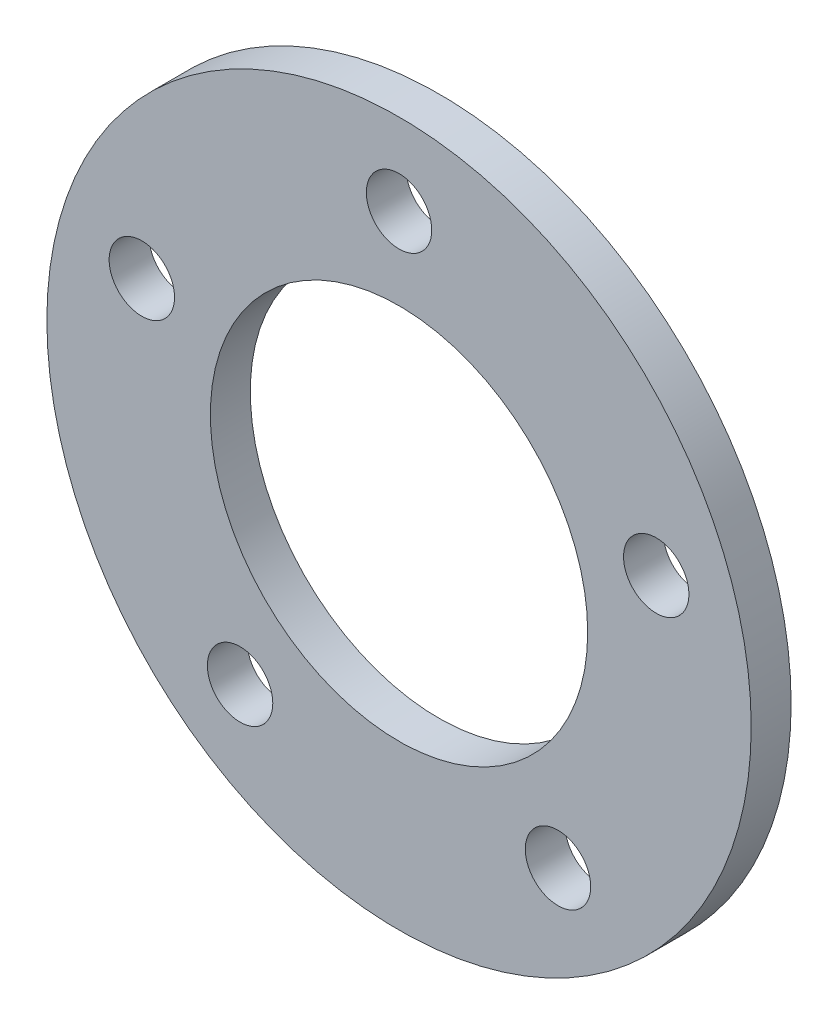
SolidWorks part; units mm, degrees
material "6061 Alloy"
ref_plane "Front Plane" through (0, 0, 0) normal (0, 0, 1) x (1, 0, 0)
ref_plane "Top Plane" through (0, 0, 0) normal (0, 1, 0) x (1, 0, 0)
ref_plane "Right Plane" through (0, 0, 0) normal (1, 0, 0) x (0, 0, -1)
sketch "Sketch1" plane through (0, 0, 0) normal (0, 0, 1) x (1, 0, 0)
  line L0 (0, 0) -> (0, 21.5) construction
  circle A0 centre (0, 0) radius 15
  circle A1 centre (0, 0) radius 28
  circle A2 centre (0, 21.5) radius 2.6
  circle A3 centre (20.4477, 6.6439) radius 2.6
  circle A4 centre (12.6374, -17.3939) radius 2.6
  circle A5 centre (-12.6374, -17.3939) radius 2.6
  circle A6 centre (-20.4477, 6.6439) radius 2.6
  dimension "D1" = 30
  dimension "D2" = 56
  dimension "D4" = 5.2
  dimension "D3" = 21.5
  dimension "D5" = 5
extrude "Boss-Extrude1" add sketch "Sketch1" along normal blind 3.175
equation "\"D1@Boss-Extrude1\"=1/8in"
